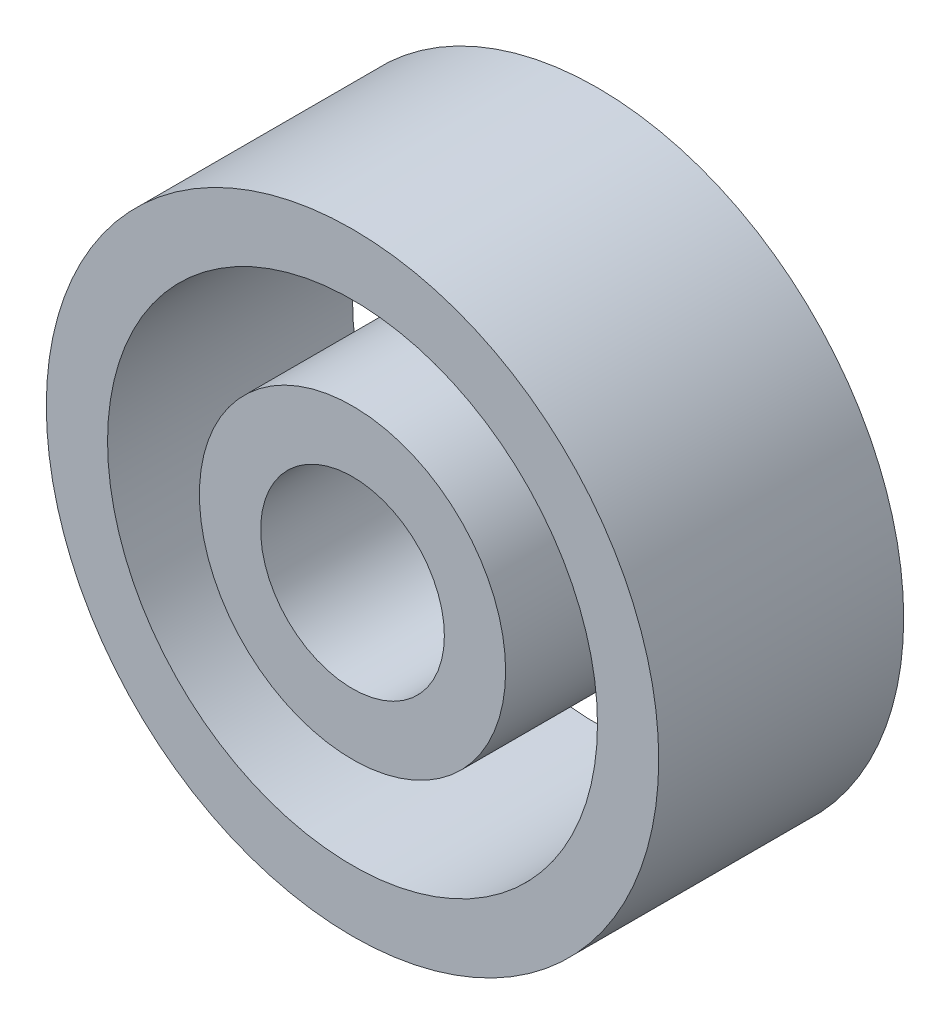
SolidWorks part; units mm, degrees
ref_plane "前视基准面" through (0, 0, 0) normal (0, 0, 1) x (1, 0, 0)
ref_plane "上视基准面" through (0, 0, 0) normal (0, 1, 0) x (1, 0, 0)
ref_plane "右视基准面" through (0, 0, 0) normal (1, 0, 0) x (0, 0, -1)
other "Configuration Table"
sketch "草图1" plane through (0, 0, 0) normal (0, 0, 1) x (1, 0, 0)
  circle A0 centre (0, 0) radius 5
  circle A1 centre (0, 0) radius 4
extrude "凸台-拉伸1" add sketch "草图1" along normal mid plane 4
sketch "草图2" plane through (0, 0, 0) normal (0, 0, 1) x (1, 0, 0)
  circle A0 centre (0, 0) radius 2.5
  circle A1 centre (0, 0) radius 1.5
extrude "凸台-拉伸2" add sketch "草图2" along normal mid plane 4
